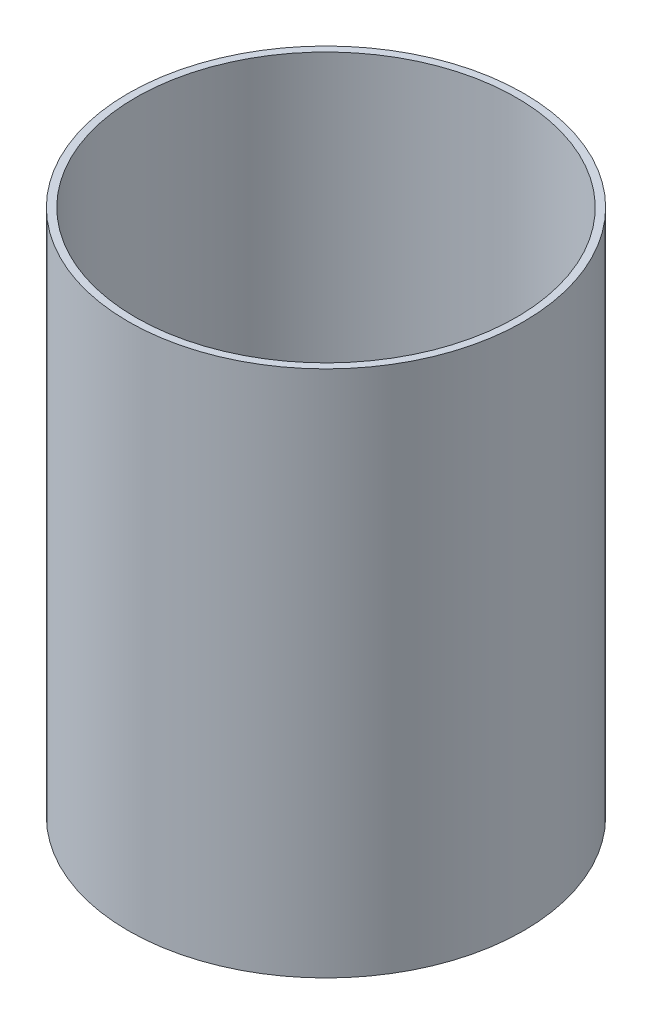
SolidWorks part; units mm, degrees
material "E-Glass Fiber"
ref_plane "Front Plane" through (0, 0, 0) normal (0, 0, 1) x (1, 0, 0)
ref_plane "Top Plane" through (0, 0, 0) normal (0, 1, 0) x (1, 0, 0)
ref_plane "Right Plane" through (0, 0, 0) normal (1, 0, 0) x (0, 0, -1)
sketch "Coupler Profile" plane through (0, 0, 0) normal (0, 1, 0) x (1, 0, 0)
  circle A0 centre (0, 0) radius 73.3425
  circle A1 centre (0, 0) radius 76.1746
  dimension "D1" = 146.685
  dimension "D2" = 152.3492
extrude "Coupler Body" add sketch "Coupler Profile" along normal blind 203.2
equation "\"Length\"= 8"
equation "\"Outer Diameter\"= 5.998"
equation "\"Inner Diameter\"= 5.775"
equation "\"Wall Thickness\"= 0.111"
equation "\"D1@Coupler Profile\"=\"Inner Diameter\""
equation "\"D2@Coupler Profile\"=\"Outer Diameter\""
equation "\"D1@Coupler Body\"=\"Length\""
